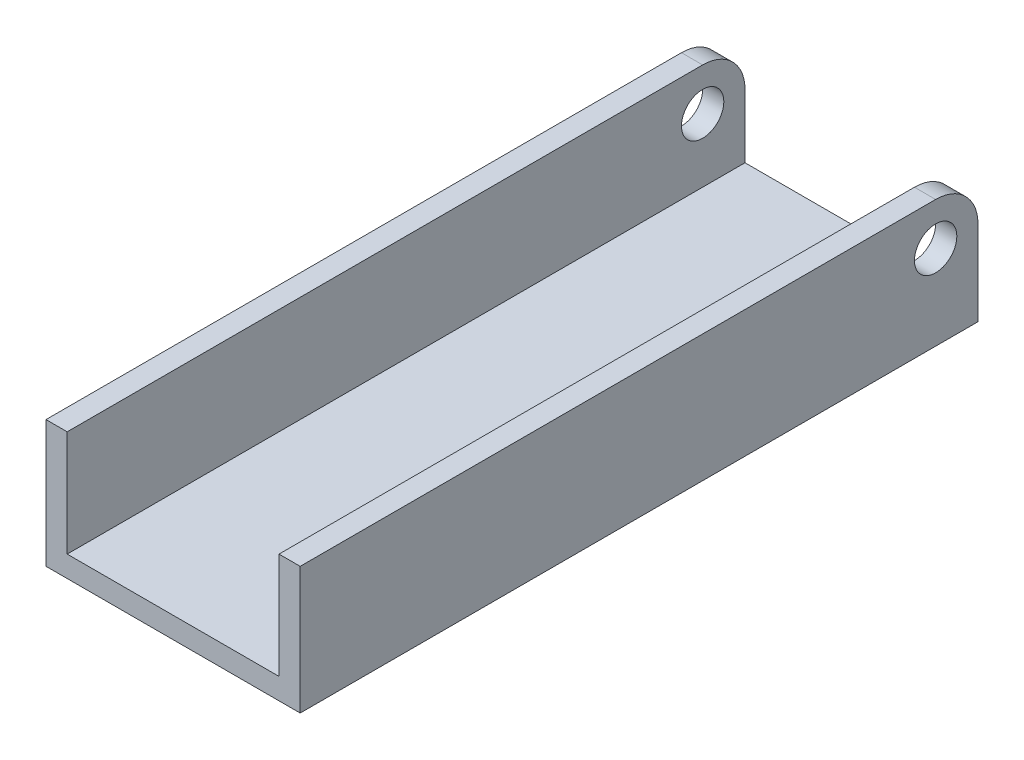
SolidWorks part; units mm, degrees
material "1060 Alloy"
ref_plane "Front" through (0, 0, 0) normal (0, 0, 1) x (1, 0, 0)
ref_plane "Top" through (0, 0, 0) normal (0, 1, 0) x (1, 0, 0)
ref_plane "Right" through (0, 0, 0) normal (1, 0, 0) x (0, 0, -1)
sketch "Sketch1" plane through (0, 0, 0) normal (0, 0, 1) x (1, 0, 0)
  line L0 (17.4625, 9.525) -> (17.4625, 1.5875)
  line L1 (0, 0) -> (19.05, 0)
  line L2 (0, 0) -> (0, 9.525)
  line L7 (0, 9.525) -> (1.5875, 9.525)
  line L9 (17.4625, 9.525) -> (19.05, 9.525)
  line L12 (19.05, 9.525) -> (19.05, 0)
  line L13 (17.4625, 1.5875) -> (1.5875, 1.5875)
  line L14 (1.5875, 1.5875) -> (1.5875, 9.525)
  dimension "D1" = 1.5875
  dimension "D2" = 1.5875
  dimension "D3" = 9.525
  dimension "D4" = 19.05
extrude "Boss-Extrude1" add sketch "Sketch1" along normal blind 50.8
hole_wizard "1/8 (0.125) Diameter Hole1" positions "Sketch2" profile "Sketch3" hole size "1/8" standard "ANSI Inch" end condition through all
sketch "Sketch2" plane through (19.05, 0, 0) normal (1, 0, 0) x (0, 0, -1)
  line L0 (0, 0) -> (0, 9.525) construction
  line L1 (-50.8, 9.525) -> (0, 9.525) construction
  point P0 (-3.175, 6.35)
  dimension "D1" = 3.175
  dimension "D2" = 3.175
sketch "Sketch3" plane through (19.05, 6.35, 3.175) normal (0, 1, 0) x (0, 0, -1)
  line L0 (0, 0) -> (0, 19.05)
  line L1 (0, 19.05) -> (1.5875, 19.05)
  line L2 (1.5875, 19.05) -> (1.5875, 0)
  line L5 (1.5875, 0) -> (0, 0)
  line L11 (0, -6.35) -> (0, 107.95) construction
  dimension "Thru Hole Dia." = 3.175
  dimension "Thru Hole Depth" = 19.05
fillet "Fillet2" radius 3.175 2 edges at (0.7937, 9.525, 0) (18.2563, 9.525, 0)
